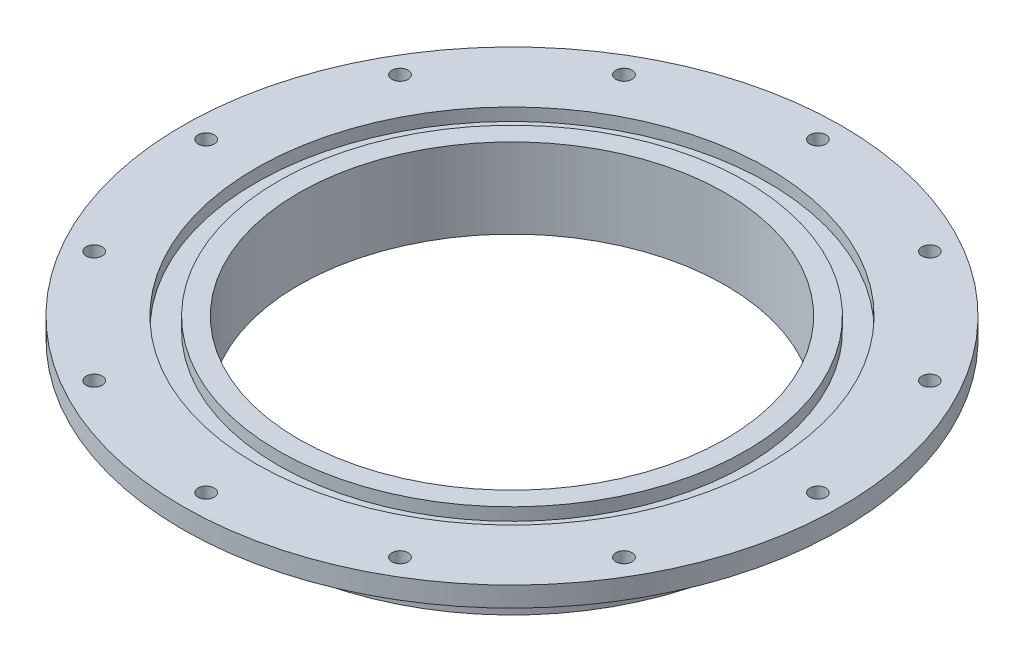
SolidWorks part; units mm, degrees
ref_plane "Front Plane" through (0, 0, 0) normal (0, 0, 1) x (1, 0, 0)
ref_plane "Top Plane" through (0, 0, 0) normal (0, 1, 0) x (1, 0, 0)
ref_plane "Right Plane" through (0, 0, 0) normal (1, 0, 0) x (0, 0, -1)
sketch "Sketch1" plane through (0, 0, 0) normal (0, 1, 0) x (1, 0, 0)
  circle A0 centre (0, 0) radius 80.518
  circle A1 centre (0, 0) radius 67.818
  dimension "D1" = 161.036
  dimension "D2" = 12.7
extrude "Inner Cylinder" add sketch "Sketch1" along normal blind 19.05
sketch "Sketch2" plane through (0, 19.05, 0) normal (0, 1, 0) x (1, 0, 0)
  circle A0 centre (0, 0) radius 67.818
  circle A1 centre (0, 0) radius 67.818 construction
  circle A2 centre (0, 0) radius 104.775
  dimension "D1" = 209.55
extrude "Flange" add sketch "Sketch2" along normal blind 6.35
sketch "Sketch4" plane through (0, 25.4, 0) normal (0, 1, 0) x (1, 0, 0)
  line L0 (0, 75.8825) -> (0, 81.2165) construction
  circle A3 centre (0, 0) radius 81.407
  circle A4 centre (0, 0) radius 74.295
  point P7 (0, 78.5495)
  dimension "D1" = 148.59
  dimension "D2" = 7.112
  dimension "D3" = 2.667
extrude "Groove" cut sketch "Sketch4" against normal blind 3.9878
sketch "Sketch5" plane through (0, 25.4, 0) normal (0, 1, 0) x (1, 0, 0)
  line L0 (89.7255, 0) -> (104.775, 0) construction
  circle A0 centre (0, 0) radius 97.2503 construction
  circle A1 centre (0, -97.2503) radius 3.175 construction
  circle A3 centre (0, -97.2503) radius 2.5527
  circle A6 centre (0, 0) radius 89.7255 construction
  circle A7 centre (0, 0) radius 104.775 construction
  point P9 (97.2503, 0)
  dimension "D1" = 5.1054
  dimension "D2" = 179.451
  dimension "D3" = 6.35
extrude "Screw Holes" cut sketch "Sketch5" against normal up to surface (6.35 mm away) up to face at (0, 19.05, 80.518)
pattern_circular "CirPattern1" count 12 over 360 about axis through (0, 0, 0) along (0, 1, 0) of "Screw Holes"
sketch "Sketch6" plane through (0, 25.4, 0) normal (0, 1, 0) x (1, 0, 0)
  circle A0 centre (0, 0) radius 89.7255
  dimension "D1" = 179.451
ref_plane "Plane1" through (0, 9.525, 0) normal (0, -1, 0) x (-1, 0, 0)
sketch "Sketch7" plane through (0, 9.525, 0) normal (0, -1, 0) x (-1, 0, 0)
  circle A0 centre (0, 0) radius 80.518
  circle A1 centre (0, 0) radius 80.518 construction
  circle A2 centre (0, 0) radius 76.1746
  dimension "D1" = 4.3434
extrude "Cut-Extrude1" cut sketch "Sketch7" against normal blind 3.6068 and the other way blind 3.6068
